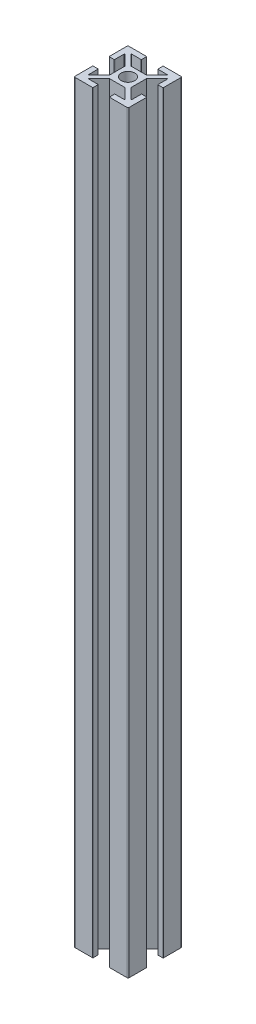
SolidWorks part; units mm, degrees
ref_plane "Front Plane" through (0, 0, 0) normal (0, 0, 1) x (1, 0, 0)
ref_plane "Top Plane" through (0, 0, 0) normal (0, 1, 0) x (1, 0, 0)
ref_plane "Right Plane" through (0, 0, 0) normal (1, 0, 0) x (0, 0, -1)
sketch "Sketch1" plane through (0, 0, 0) normal (0, 1, 0) x (1, 0, 0)
  line L0 (-9.8963, 3) -> (-8.1963, 3)
  line L3 (-3.1963, 10) -> (-9.6963, 10)
  line L4 (-10.0463, 3.15) -> (-10.0463, 9.65)
  line L7 (2.9332, 4) -> (-2.9332, 4)
  line L8 (-4, -2.9454) -> (-4, 2.9454)
  line L9 (-8.0463, 3.15) -> (-8.0463, 6.5862)
  line L10 (-6.6144, 8) -> (-3.1963, 8)
  line L11 (-3.0463, 8.15) -> (-3.0463, 9.85)
  line L12 (-8.0463, 8) -> (-4, 4) construction
  line L13 (-7.7908, 6.6929) -> (-4, 2.9454)
  line L14 (-6.7198, 7.7433) -> (-2.9332, 4)
  line L15 (8.0463, 8) -> (4, 4) construction
  line L22 (0, 0) -> (0, 11.6886) construction
  line L25 (0, 0) -> (-14.9841, 0) construction
  line L27 (6.7198, 7.7433) -> (2.9332, 4)
  line L28 (7.7908, 6.6929) -> (4, 2.9454)
  line L46 (3.0463, 8.15) -> (3.0463, 9.85)
  line L47 (6.6144, 8) -> (3.1963, 8)
  line L48 (8.0463, 3.15) -> (8.0463, 6.5862)
  line L49 (4, -2.9454) -> (4, 2.9454)
  line L50 (10.0463, 3.15) -> (10.0463, 9.65)
  line L51 (3.1963, 10) -> (9.6963, 10)
  line L52 (9.8963, 3) -> (8.1963, 3)
  line L53 (8.0463, -8) -> (4, -4) construction
  line L54 (-8.0463, -8) -> (-4, -4) construction
  line L55 (9.8963, -3) -> (8.1963, -3)
  line L56 (3.1963, -10) -> (9.6963, -10)
  line L57 (10.0463, -3.15) -> (10.0463, -9.65)
  line L58 (8.0463, -3.15) -> (8.0463, -6.5862)
  line L59 (6.6144, -8) -> (3.1963, -8)
  line L60 (3.0463, -8.15) -> (3.0463, -9.85)
  line L61 (7.7908, -6.6929) -> (4, -2.9454)
  line L62 (6.7198, -7.7433) -> (2.9332, -4)
  line L63 (-6.7198, -7.7433) -> (-2.9332, -4)
  line L64 (-7.7908, -6.6929) -> (-4, -2.9454)
  line L65 (-3.0463, -8.15) -> (-3.0463, -9.85)
  line L66 (-6.6144, -8) -> (-3.1963, -8)
  line L67 (-8.0463, -3.15) -> (-8.0463, -6.5862)
  line L68 (2.9332, -4) -> (-2.9332, -4)
  line L69 (-10.0463, -3.15) -> (-10.0463, -9.65)
  line L70 (-3.1963, -10) -> (-9.6963, -10)
  line L71 (-9.8963, -3) -> (-8.1963, -3)
  circle A0 centre (0, 0) radius 2.5
  arc A1 (-10.0463, 9.65) -> (-9.6963, 10) centre (-9.6963, 9.65) cw
  arc A2 (-9.8963, 3) -> (-10.0463, 3.15) centre (-9.8963, 3.15) cw
  arc A3 (-8.1963, 3) -> (-8.0463, 3.15) centre (-8.1963, 3.15) ccw
  arc A4 (-3.1963, 10) -> (-3.0463, 9.85) centre (-3.1963, 9.85) cw
  arc A5 (-3.1963, 8) -> (-3.0463, 8.15) centre (-3.1963, 8.15) ccw
  arc A6 (-6.7198, 7.7433) -> (-6.6144, 8) centre (-6.6144, 7.85) cw
  arc A7 (-7.7908, 6.6929) -> (-8.0463, 6.5862) centre (-7.8963, 6.5862) ccw
  arc A8 (7.7908, 6.6929) -> (8.0463, 6.5862) centre (7.8963, 6.5862) cw
  arc A9 (6.7198, 7.7433) -> (6.6144, 8) centre (6.6144, 7.85) ccw
  arc A10 (3.1963, 8) -> (3.0463, 8.15) centre (3.1963, 8.15) cw
  arc A11 (3.1963, 10) -> (3.0463, 9.85) centre (3.1963, 9.85) ccw
  arc A12 (8.1963, 3) -> (8.0463, 3.15) centre (8.1963, 3.15) cw
  arc A13 (9.8963, 3) -> (10.0463, 3.15) centre (9.8963, 3.15) ccw
  arc A14 (10.0463, 9.65) -> (9.6963, 10) centre (9.6963, 9.65) ccw
  arc A15 (10.0463, -9.65) -> (9.6963, -10) centre (9.6963, -9.65) cw
  arc A16 (9.8963, -3) -> (10.0463, -3.15) centre (9.8963, -3.15) cw
  arc A17 (8.1963, -3) -> (8.0463, -3.15) centre (8.1963, -3.15) ccw
  arc A18 (3.1963, -10) -> (3.0463, -9.85) centre (3.1963, -9.85) cw
  arc A19 (3.1963, -8) -> (3.0463, -8.15) centre (3.1963, -8.15) ccw
  arc A20 (6.7198, -7.7433) -> (6.6144, -8) centre (6.6144, -7.85) cw
  arc A21 (7.7908, -6.6929) -> (8.0463, -6.5862) centre (7.8963, -6.5862) ccw
  arc A22 (-7.7908, -6.6929) -> (-8.0463, -6.5862) centre (-7.8963, -6.5862) cw
  arc A23 (-6.7198, -7.7433) -> (-6.6144, -8) centre (-6.6144, -7.85) ccw
  arc A24 (-3.1963, -8) -> (-3.0463, -8.15) centre (-3.1963, -8.15) cw
  arc A25 (-3.1963, -10) -> (-3.0463, -9.85) centre (-3.1963, -9.85) ccw
  arc A26 (-8.1963, -3) -> (-8.0463, -3.15) centre (-8.1963, -3.15) cw
  arc A27 (-9.8963, -3) -> (-10.0463, -3.15) centre (-9.8963, -3.15) ccw
  arc A28 (-10.0463, -9.65) -> (-9.6963, -10) centre (-9.6963, -9.65) ccw
  point P8 (-10.0463, 10)
  point P27 (-10.0463, 3)
  point P30 (3.0463, 8)
  point P31 (10.0463, -10)
  point P50 (4, 0)
  point P55 (-8.0463, 3)
  point P58 (-3.0463, 10)
  point P61 (-3.0463, 8)
  point P63 (0, 4)
  point P65 (3.0463, 10)
  point P66 (8.0463, 3)
  point P67 (10.0463, 3)
  point P68 (10.0463, 10)
  point P118 (-4, 0)
  point P119 (10.0463, -3)
  point P120 (8.0463, -3)
  point P121 (3.0463, -10)
  point P122 (0, -4)
  point P123 (-3.0463, -8)
  point P124 (-3.0463, -10)
  point P125 (-8.0463, -3)
  point P126 (3.0463, -8)
  point P127 (-10.0463, -3)
  point P128 (-10.0463, -10)
  dimension "D2" = 0.35
  dimension "D3" = 0.15
  dimension "D4" = 0.15
  dimension "D5" = 0.15
  dimension "D12" = 0.15
  dimension "D13" = 0.15
  dimension "D14" = 0.15
  dimension "D6" = 2
  dimension "D7" = 7
  dimension "D8" = 7
  dimension "D9" = 2
  dimension "D10" = 0.75
  dimension "D11" = 0.75
extrude "Boss-Extrude2" add sketch "Sketch1" along normal blind 280
